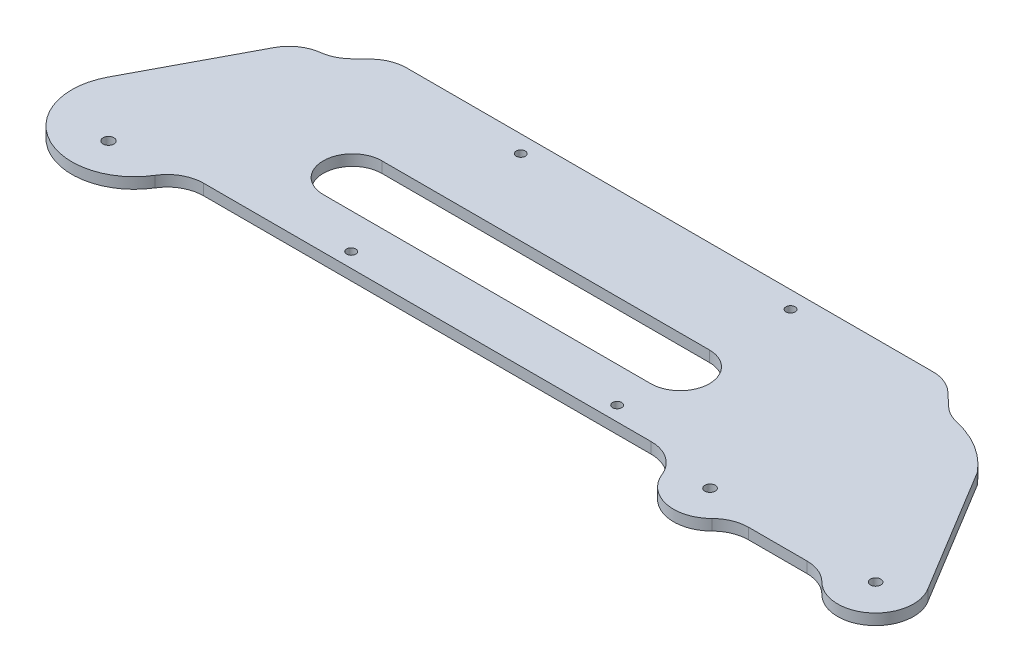
SolidWorks part; units mm, degrees
ref_plane "Front Plane" through (0, 0, 0) normal (0, 0, 1) x (1, 0, 0)
ref_plane "Top Plane" through (0, 0, 0) normal (0, 1, 0) x (1, 0, 0)
ref_plane "Right Plane" through (0, 0, 0) normal (1, 0, 0) x (0, 0, -1)
sketch "Sketch1" plane through (0, 0, 0) normal (0, 1, 0) x (1, 0, 0)
  line L0 (-218.725, 0) -> (190.3461, 0) construction
  line L1 (226.9351, 0) -> (-298.3869, 0)
  line L2 (-79.2871, 15.1404) -> (-60.8343, 50)
  line L3 (-44.5468, 58.2347) -> (-53.2755, 50)
  line L4 (-44.5468, 58.2347) -> (107.7684, 58.2347)
  line L5 (107.7684, 58.2347) -> (116.4971, 50)
  line L6 (-159.8292, -10) -> (178.5073, -10) construction
  line L7 (110.4701, -3.9888) -> (158.6997, -3.9888)
  line L8 (154.6293, 6.1115) -> (133.8757, 40.3405)
  line L9 (-53.2755, 50) -> (-60.8343, 50)
  line L10 (-46.8636, 50) -> (133.2144, 50) construction
  line L11 (-47.527, 3) -> (90.5945, 3)
  circle A0 centre (-64.1497, 7.1275) radius 17.1275
  circle A1 centre (-64.0837, 0) radius 1.5
  circle A2 centre (100.9163, 0) radius 1.42
  circle A3 centre (100.9163, 0.5977) radius 10.5977
  circle A4 centre (113.2017, 23.6083) radius 26.5966
  circle A5 centre (145.9163, 0.4117) radius 10.4117
  circle A6 centre (145.9163, 0.4117) radius 1.42
  point P32 (-79.2871, 15.1404)
  dimension "D4" = 210
  dimension "D5" = 3
  dimension "D6" = 2.84
  dimension "D7" = 2.84
  dimension "D1" = 45
  dimension "D2" = 3
  dimension "D3" = 10
  dimension "D8" = 12
  dimension "D9" = 12
  dimension "D10" = 165
extrude "Boss-Extrude1" add sketch "Sketch1" along normal blind 3
sketch "Sketch2" plane through (0, 3, 0) normal (0, 1, 0) x (1, 0, 0)
  line L0 (67.9726, 24.7357) -> (-21.8765, 24.7357) construction
  line L1 (67.9726, 16.7054) -> (-21.8765, 16.7054)
  line L2 (67.9726, 32.7659) -> (-21.8765, 32.7659)
  arc A0 (67.9726, 16.7054) -> (67.9726, 32.7659) centre (67.9726, 24.7357) ccw
  arc A1 (-21.8765, 32.7659) -> (-21.8765, 16.7054) centre (-21.8765, 24.7357) ccw
  point P2 (23.048, 24.7357)
extrude "Cut-Extrude1" cut sketch "Sketch2" against normal blind 10
sketch "Sketch3" plane through (0, 3, 0) normal (0, 1, 0) x (1, 0, 0)
  circle A0 centre (-4.515, 7) radius 1.25
  circle A1 centre (68.4469, 7) radius 1.25
  circle A2 centre (-4.515, 53.5184) radius 1.25
  circle A3 centre (69.4807, 53.5184) radius 1.25
  dimension "D1" = 2.5
  dimension "D2" = 2.5
  dimension "D5" = 2.5
  dimension "D6" = 2.5
extrude "Cut-Extrude2" cut sketch "Sketch3" against normal blind 4
fillet "Fillet3" radius 10 4 edges at (136.4802, 1.5, 3.9888) (110.4701, 1.5, 3.9888) (90.5945, 1.5, -3) (-47.527, 1.5, -3)
fillet "Fillet5" radius 10 4 edges at (-53.2755, 1.5, -50) (107.7684, 1.5, -58.2347) (116.4971, 1.5, -50) (-44.5468, 1.5, -58.2347)
fillet "Fillet6" radius 10 1 edges at (-60.8343, 1.5, -50)
